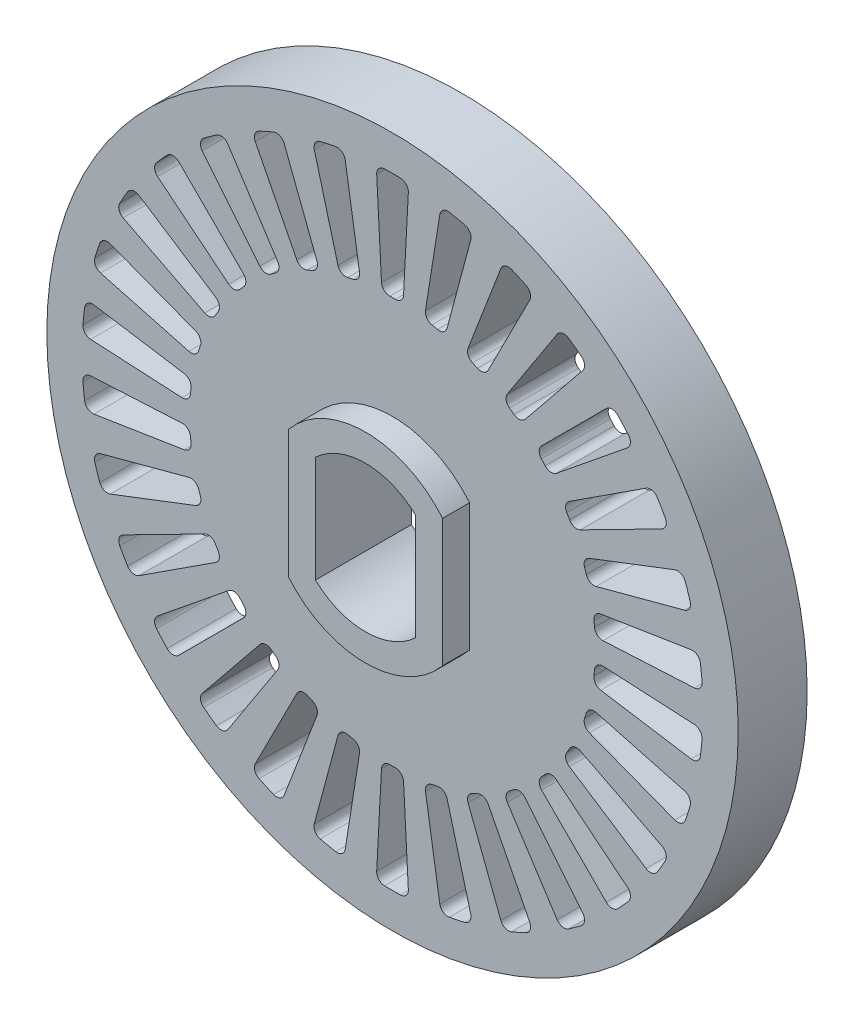
SolidWorks part; units mm, degrees
ref_plane "Plano frontal" through (0, 0, 0) normal (0, 0, 1) x (1, 0, 0)
ref_plane "Plano superior" through (0, 0, 0) normal (0, 1, 0) x (1, 0, 0)
ref_plane "Plano direito" through (0, 0, 0) normal (1, 0, 0) x (0, 0, -1)
sketch "Esboço1" plane through (0, 0, 0) normal (0, 0, 1) x (1, 0, 0)
  line L2 (-1.85, 1.9666) -> (-1.85, -1.9666)
  line L4 (1.85, 1.9666) -> (1.85, -1.9666)
  circle A0 centre (0, 0) radius 12.78
  arc A1 (-1.85, -1.9666) -> (1.85, -1.9666) centre (0, 0) ccw
  arc A2 (1.85, 1.9666) -> (-1.85, 1.9666) centre (0, 0) ccw
  dimension "D1" = 25.56
  dimension "D2" = 5.4
extrude "Ressalto-extrusão1" add sketch "Esboço1" along normal blind 2.55
sketch "Esboço2" plane through (0, 0, 0) normal (0, 0, 1) x (1, 0, 0)
  line L0 (-1.85, 1.9666) -> (-1.85, -1.9666) construction
  line L1 (1.85, -1.9666) -> (1.85, 1.9666) construction
  line L2 (1.85, -1.9666) -> (1.85, 1.9666)
  line L3 (-1.85, 1.9666) -> (-1.85, -1.9666)
  line L4 (-2.85, 2.3596) -> (-2.85, -2.3596)
  line L5 (2.85, -2.3596) -> (2.85, 2.3596)
  arc A0 (1.85, 1.9666) -> (-1.85, 1.9666) centre (0, 0) ccw construction
  circle A1 centre (0, 0) radius 12.78
  circle A2 centre (0, 0) radius 12.78
  arc A3 (-1.85, -1.9666) -> (1.85, -1.9666) centre (0, 0) ccw construction
  arc A4 (-1.85, -1.9666) -> (1.85, -1.9666) centre (0, 0) ccw
  arc A5 (1.85, 1.9666) -> (-1.85, 1.9666) centre (0, 0) ccw
  arc A6 (2.85, 2.3596) -> (-2.85, 2.3596) centre (0, 0) ccw
  arc A7 (-2.85, -2.3596) -> (2.85, -2.3596) centre (0, 0) ccw
  arc M21 (-1.85, -1.9666) -> (1.85, -1.9666) centre (0, 0) ccw
  line M22 (1.85, -1.9666) -> (1.85, 1.9666)
  arc M23 (1.85, 1.9666) -> (-1.85, 1.9666) centre (0, 0) ccw
  line M24 (-1.85, 1.9666) -> (-1.85, -1.9666)
  dimension "D1" = 0
  dimension "D2" = 1
extrude "Ressalto-extrusão2" add sketch "Esboço2" along normal blind 3.55 contours A7 L4 A6 L5 M24 M21 M22 M23
sketch "Esboço3" plane through (0, 0, 2.55) normal (0, 0, 1) x (1, 0, 0)
  line L0 (0, 0) -> (0, 12.78) construction
  line L1 (0.4079, 7.7835) -> (0.5849, 11.1607)
  line L2 (-0.4079, 7.7835) -> (-0.5849, 11.1607)
  line L3 (2.0173, 7.5286) -> (2.8926, 10.7952)
  line L4 (1.2193, 7.6983) -> (1.7483, 11.0384)
  line L5 (3.5385, 6.9447) -> (5.0738, 9.9579)
  line L6 (2.7932, 7.2765) -> (4.0051, 10.4337)
  line L7 (4.9051, 6.0573) -> (7.0333, 8.6854)
  line L8 (4.245, 6.5368) -> (6.0869, 9.373)
  line L9 (6.0573, 4.9051) -> (8.6854, 7.0333)
  line L10 (5.5114, 5.5114) -> (7.9026, 7.9026)
  line L11 (6.9447, 3.5385) -> (9.9579, 5.0738)
  line L12 (6.5368, 4.245) -> (9.373, 6.0869)
  line L13 (7.5286, 2.0173) -> (10.7952, 2.8926)
  line L14 (7.2765, 2.7932) -> (10.4337, 4.0051)
  line L15 (7.7835, 0.4079) -> (11.1607, 0.5849)
  line L16 (7.6983, 1.2193) -> (11.0384, 1.7483)
  line L17 (7.6983, -1.2193) -> (11.0384, -1.7483)
  line L18 (7.7835, -0.4079) -> (11.1607, -0.5849)
  line L19 (7.2765, -2.7932) -> (10.4337, -4.0051)
  line L20 (7.5286, -2.0173) -> (10.7952, -2.8926)
  line L21 (6.5368, -4.245) -> (9.373, -6.0869)
  line L22 (6.9447, -3.5385) -> (9.9579, -5.0738)
  line L23 (5.5114, -5.5114) -> (7.9026, -7.9026)
  line L24 (6.0573, -4.9051) -> (8.6854, -7.0333)
  line L25 (4.245, -6.5368) -> (6.0869, -9.373)
  line L26 (4.9051, -6.0573) -> (7.0333, -8.6854)
  line L27 (2.7932, -7.2765) -> (4.0051, -10.4337)
  line L28 (3.5385, -6.9447) -> (5.0738, -9.9579)
  line L29 (1.2193, -7.6983) -> (1.7483, -11.0384)
  line L30 (2.0173, -7.5286) -> (2.8926, -10.7952)
  line L31 (-0.4079, -7.7835) -> (-0.5849, -11.1607)
  line L32 (0.4079, -7.7835) -> (0.5849, -11.1607)
  line L33 (-2.0173, -7.5286) -> (-2.8926, -10.7952)
  line L34 (-1.2193, -7.6983) -> (-1.7483, -11.0384)
  line L35 (-3.5385, -6.9447) -> (-5.0738, -9.9579)
  line L36 (-2.7932, -7.2765) -> (-4.0051, -10.4337)
  line L37 (-4.9051, -6.0573) -> (-7.0333, -8.6854)
  line L38 (-4.245, -6.5368) -> (-6.0869, -9.373)
  line L39 (-6.0573, -4.9051) -> (-8.6854, -7.0333)
  line L40 (-5.5114, -5.5114) -> (-7.9026, -7.9026)
  line L41 (-6.9447, -3.5385) -> (-9.9579, -5.0738)
  line L42 (-6.5368, -4.245) -> (-9.373, -6.0869)
  line L43 (-7.5286, -2.0173) -> (-10.7952, -2.8926)
  line L44 (-7.2765, -2.7932) -> (-10.4337, -4.0051)
  line L45 (-7.7835, -0.4079) -> (-11.1607, -0.5849)
  line L46 (-7.6983, -1.2193) -> (-11.0384, -1.7483)
  line L47 (-7.6983, 1.2193) -> (-11.0384, 1.7483)
  line L48 (-7.7835, 0.4079) -> (-11.1607, 0.5849)
  line L49 (-7.2765, 2.7932) -> (-10.4337, 4.0051)
  line L50 (-7.5286, 2.0173) -> (-10.7952, 2.8926)
  line L51 (-6.5368, 4.245) -> (-9.373, 6.0869)
  line L52 (-6.9447, 3.5385) -> (-9.9579, 5.0738)
  line L53 (-5.5114, 5.5114) -> (-7.9026, 7.9026)
  line L54 (-6.0573, 4.9051) -> (-8.6854, 7.0333)
  line L55 (-4.245, 6.5368) -> (-6.0869, 9.373)
  line L56 (-4.9051, 6.0573) -> (-7.0333, 8.6854)
  line L57 (-2.7932, 7.2765) -> (-4.0051, 10.4337)
  line L58 (-3.5385, 6.9447) -> (-5.0738, 9.9579)
  line L59 (-1.2193, 7.6983) -> (-1.7483, 11.0384)
  line L60 (-2.0173, 7.5286) -> (-2.8926, 10.7952)
  circle A0 centre (0, 0) radius 12.78 construction
  arc A1 (0.293, 11.4763) -> (-0.293, 11.4763) centre (0, 0) ccw
  arc A2 (0.1042, 7.4993) -> (-0.1042, 7.4993) centre (0, 0) ccw
  arc A3 (1.85, 1.9666) -> (-1.85, 1.9666) centre (0, 0) ccw construction
  arc A4 (0.4079, 7.7835) -> (0.1042, 7.4993) centre (0.1083, 7.7992) cw
  arc A5 (-0.4079, 7.7835) -> (-0.1042, 7.4993) centre (-0.1083, 7.7992) ccw
  arc A6 (0.5849, 11.1607) -> (0.293, 11.4763) centre (0.2853, 11.1764) ccw
  arc A7 (-0.5849, 11.1607) -> (-0.293, 11.4763) centre (-0.2853, 11.1764) cw
  arc A9 (2.6726, 11.1646) -> (2.0995, 11.2864) centre (0, 0) ccw
  arc A10 (1.6611, 7.3137) -> (1.4573, 7.3571) centre (0, 0) ccw
  arc A11 (2.0173, 7.5286) -> (1.6611, 7.3137) centre (1.7275, 7.6063) cw
  arc A12 (1.2193, 7.6983) -> (1.4573, 7.3571) centre (1.5156, 7.6513) ccw
  arc A13 (2.8926, 10.7952) -> (2.6726, 11.1646) centre (2.6028, 10.8728) ccw
  arc A14 (1.7483, 11.0384) -> (2.0995, 11.2864) centre (2.0446, 10.9914) cw
  arc A15 (4.9355, 10.3649) -> (4.4002, 10.6032) centre (0, 0) ccw
  arc A16 (3.1454, 6.8086) -> (2.9551, 6.8933) centre (0, 0) ccw
  arc A17 (3.5385, 6.9447) -> (3.1454, 6.8086) centre (3.2712, 7.0809) cw
  arc A18 (2.7932, 7.2765) -> (2.9551, 6.8933) centre (3.0733, 7.169) ccw
  arc A19 (5.0738, 9.9579) -> (4.9355, 10.3649) centre (4.8065, 10.0941) ccw
  arc A20 (4.0051, 10.4337) -> (4.4002, 10.6032) centre (4.2852, 10.3262) cw
  arc A21 (6.9826, 9.1123) -> (6.5086, 9.4567) centre (0, 0) ccw
  arc A22 (4.4922, 6.0058) -> (4.3237, 6.1283) centre (0, 0) ccw
  arc A23 (4.9051, 6.0573) -> (4.4922, 6.0058) centre (4.6719, 6.246) cw
  arc A24 (4.245, 6.5368) -> (4.3237, 6.1283) centre (4.4966, 6.3734) ccw
  arc A25 (7.0333, 8.6854) -> (6.9826, 9.1123) centre (6.8001, 8.8742) ccw
  arc A26 (6.0869, 9.373) -> (6.5086, 9.4567) centre (6.3385, 9.2096) cw
  arc A27 (8.7246, 7.4614) -> (8.3325, 7.8968) centre (0, 0) ccw
  arc A28 (5.6427, 4.9406) -> (5.5033, 5.0954) centre (0, 0) ccw
  arc A29 (6.0573, 4.9051) -> (5.6427, 4.9406) centre (5.8685, 5.1382) cw
  arc A30 (5.5114, 5.5114) -> (5.5033, 5.0954) centre (5.7235, 5.2992) ccw
  arc A31 (8.6854, 7.0333) -> (8.7246, 7.4614) centre (8.4966, 7.2664) ccw
  arc A32 (7.9026, 7.9026) -> (8.3325, 7.8968) centre (8.1147, 7.6905) cw
  arc A33 (10.0852, 5.4844) -> (9.7922, 5.9919) centre (0, 0) ccw
  arc A34 (6.5466, 3.6594) -> (6.4425, 3.8398) centre (0, 0) ccw
  arc A35 (6.9447, 3.5385) -> (6.5466, 3.6594) centre (6.8085, 3.8058) cw
  arc A36 (6.5368, 4.245) -> (6.4425, 3.8398) centre (6.7002, 3.9934) ccw
  arc A37 (9.9579, 5.0738) -> (10.0852, 5.4844) centre (9.8217, 5.3411) ccw
  arc A38 (9.373, 6.0869) -> (9.7922, 5.9919) centre (9.5364, 5.8353) cw
  arc A39 (11.0051, 3.2677) -> (10.824, 3.825) centre (0, 0) ccw
  arc A40 (7.1644, 2.2183) -> (7.1, 2.4165) centre (0, 0) ccw
  arc A41 (7.5286, 2.0173) -> (7.1644, 2.2183) centre (7.451, 2.3071) cw
  arc A42 (7.2765, 2.7932) -> (7.1, 2.4165) centre (7.384, 2.5131) ccw
  arc A43 (10.7952, 2.8926) -> (11.0051, 3.2677) centre (10.7175, 3.1823) ccw
  arc A44 (10.4337, 4.0051) -> (10.824, 3.825) centre (10.5412, 3.725) cw
  arc A45 (11.444, 0.9082) -> (11.3828, 1.491) centre (0, 0) ccw
  arc A46 (7.4691, 0.6803) -> (7.4473, 0.8875) centre (0, 0) ccw
  arc A47 (7.7835, 0.4079) -> (7.4691, 0.6803) centre (7.7678, 0.7075) cw
  arc A48 (7.6983, 1.2193) -> (7.4473, 0.8875) centre (7.7452, 0.923) ccw
  arc A49 (11.1607, 0.5849) -> (11.444, 0.9082) centre (11.145, 0.8845) ccw
  arc A50 (11.0384, 1.7483) -> (11.3828, 1.491) centre (11.0853, 1.452) cw
  arc A51 (11.3828, -1.491) -> (11.444, -0.9082) centre (0, 0) ccw
  arc A52 (7.4473, -0.8875) -> (7.4691, -0.6803) centre (0, 0) ccw
  arc A53 (7.6983, -1.2193) -> (7.4473, -0.8875) centre (7.7452, -0.923) cw
  arc A54 (7.7835, -0.4079) -> (7.4691, -0.6803) centre (7.7678, -0.7075) ccw
  arc A55 (11.0384, -1.7483) -> (11.3828, -1.491) centre (11.0853, -1.452) ccw
  arc A56 (11.1607, -0.5849) -> (11.444, -0.9082) centre (11.145, -0.8845) cw
  arc A57 (10.824, -3.825) -> (11.0051, -3.2677) centre (0, 0) ccw
  arc A58 (7.1, -2.4165) -> (7.1644, -2.2183) centre (0, 0) ccw
  arc A59 (7.2765, -2.7932) -> (7.1, -2.4165) centre (7.384, -2.5131) cw
  arc A60 (7.5286, -2.0173) -> (7.1644, -2.2183) centre (7.451, -2.3071) ccw
  arc A61 (10.4337, -4.0051) -> (10.824, -3.825) centre (10.5412, -3.725) ccw
  arc A62 (10.7952, -2.8926) -> (11.0051, -3.2677) centre (10.7175, -3.1823) cw
  arc A63 (9.7922, -5.9919) -> (10.0852, -5.4844) centre (0, 0) ccw
  arc A64 (6.4425, -3.8398) -> (6.5466, -3.6594) centre (0, 0) ccw
  arc A65 (6.5368, -4.245) -> (6.4425, -3.8398) centre (6.7002, -3.9934) cw
  arc A66 (6.9447, -3.5385) -> (6.5466, -3.6594) centre (6.8085, -3.8058) ccw
  arc A67 (9.373, -6.0869) -> (9.7922, -5.9919) centre (9.5364, -5.8353) ccw
  arc A68 (9.9579, -5.0738) -> (10.0852, -5.4844) centre (9.8217, -5.3411) cw
  arc A69 (8.3325, -7.8968) -> (8.7246, -7.4614) centre (0, 0) ccw
  arc A70 (5.5033, -5.0954) -> (5.6427, -4.9406) centre (0, 0) ccw
  arc A71 (5.5114, -5.5114) -> (5.5033, -5.0954) centre (5.7235, -5.2992) cw
  arc A72 (6.0573, -4.9051) -> (5.6427, -4.9406) centre (5.8685, -5.1382) ccw
  arc A73 (7.9026, -7.9026) -> (8.3325, -7.8968) centre (8.1147, -7.6905) ccw
  arc A74 (8.6854, -7.0333) -> (8.7246, -7.4614) centre (8.4966, -7.2664) cw
  arc A75 (6.5086, -9.4567) -> (6.9826, -9.1123) centre (0, 0) ccw
  arc A76 (4.3237, -6.1283) -> (4.4922, -6.0058) centre (0, 0) ccw
  arc A77 (4.245, -6.5368) -> (4.3237, -6.1283) centre (4.4966, -6.3734) cw
  arc A78 (4.9051, -6.0573) -> (4.4922, -6.0058) centre (4.6719, -6.246) ccw
  arc A79 (6.0869, -9.373) -> (6.5086, -9.4567) centre (6.3385, -9.2096) ccw
  arc A80 (7.0333, -8.6854) -> (6.9826, -9.1123) centre (6.8001, -8.8742) cw
  arc A81 (4.4002, -10.6032) -> (4.9355, -10.3649) centre (0, 0) ccw
  arc A82 (2.9551, -6.8933) -> (3.1454, -6.8086) centre (0, 0) ccw
  arc A83 (2.7932, -7.2765) -> (2.9551, -6.8933) centre (3.0733, -7.169) cw
  arc A84 (3.5385, -6.9447) -> (3.1454, -6.8086) centre (3.2712, -7.0809) ccw
  arc A85 (4.0051, -10.4337) -> (4.4002, -10.6032) centre (4.2852, -10.3262) ccw
  arc A86 (5.0738, -9.9579) -> (4.9355, -10.3649) centre (4.8065, -10.0941) cw
  arc A87 (2.0995, -11.2864) -> (2.6726, -11.1646) centre (0, 0) ccw
  arc A88 (1.4573, -7.3571) -> (1.6611, -7.3137) centre (0, 0) ccw
  arc A89 (1.2193, -7.6983) -> (1.4573, -7.3571) centre (1.5156, -7.6513) cw
  arc A90 (2.0173, -7.5286) -> (1.6611, -7.3137) centre (1.7275, -7.6063) ccw
  arc A91 (1.7483, -11.0384) -> (2.0995, -11.2864) centre (2.0446, -10.9914) ccw
  arc A92 (2.8926, -10.7952) -> (2.6726, -11.1646) centre (2.6028, -10.8728) cw
  arc A93 (-0.293, -11.4763) -> (0.293, -11.4763) centre (0, 0) ccw
  arc A94 (-0.1042, -7.4993) -> (0.1042, -7.4993) centre (0, 0) ccw
  arc A95 (-0.4079, -7.7835) -> (-0.1042, -7.4993) centre (-0.1083, -7.7992) cw
  arc A96 (0.4079, -7.7835) -> (0.1042, -7.4993) centre (0.1083, -7.7992) ccw
  arc A97 (-0.5849, -11.1607) -> (-0.293, -11.4763) centre (-0.2853, -11.1764) ccw
  arc A98 (0.5849, -11.1607) -> (0.293, -11.4763) centre (0.2853, -11.1764) cw
  arc A99 (-2.6726, -11.1646) -> (-2.0995, -11.2864) centre (0, 0) ccw
  arc A100 (-1.6611, -7.3137) -> (-1.4573, -7.3571) centre (0, 0) ccw
  arc A101 (-2.0173, -7.5286) -> (-1.6611, -7.3137) centre (-1.7275, -7.6063) cw
  arc A102 (-1.2193, -7.6983) -> (-1.4573, -7.3571) centre (-1.5156, -7.6513) ccw
  arc A103 (-2.8926, -10.7952) -> (-2.6726, -11.1646) centre (-2.6028, -10.8728) ccw
  arc A104 (-1.7483, -11.0384) -> (-2.0995, -11.2864) centre (-2.0446, -10.9914) cw
  arc A105 (-4.9355, -10.3649) -> (-4.4002, -10.6032) centre (0, 0) ccw
  arc A106 (-3.1454, -6.8086) -> (-2.9551, -6.8933) centre (0, 0) ccw
  arc A107 (-3.5385, -6.9447) -> (-3.1454, -6.8086) centre (-3.2712, -7.0809) cw
  arc A108 (-2.7932, -7.2765) -> (-2.9551, -6.8933) centre (-3.0733, -7.169) ccw
  arc A109 (-5.0738, -9.9579) -> (-4.9355, -10.3649) centre (-4.8065, -10.0941) ccw
  arc A110 (-4.0051, -10.4337) -> (-4.4002, -10.6032) centre (-4.2852, -10.3262) cw
  arc A111 (-6.9826, -9.1123) -> (-6.5086, -9.4567) centre (0, 0) ccw
  arc A112 (-4.4922, -6.0058) -> (-4.3237, -6.1283) centre (0, 0) ccw
  arc A113 (-4.9051, -6.0573) -> (-4.4922, -6.0058) centre (-4.6719, -6.246) cw
  arc A114 (-4.245, -6.5368) -> (-4.3237, -6.1283) centre (-4.4966, -6.3734) ccw
  arc A115 (-7.0333, -8.6854) -> (-6.9826, -9.1123) centre (-6.8001, -8.8742) ccw
  arc A116 (-6.0869, -9.373) -> (-6.5086, -9.4567) centre (-6.3385, -9.2096) cw
  arc A117 (-8.7246, -7.4614) -> (-8.3325, -7.8968) centre (0, 0) ccw
  arc A118 (-5.6427, -4.9406) -> (-5.5033, -5.0954) centre (0, 0) ccw
  arc A119 (-6.0573, -4.9051) -> (-5.6427, -4.9406) centre (-5.8685, -5.1382) cw
  arc A120 (-5.5114, -5.5114) -> (-5.5033, -5.0954) centre (-5.7235, -5.2992) ccw
  arc A121 (-8.6854, -7.0333) -> (-8.7246, -7.4614) centre (-8.4966, -7.2664) ccw
  arc A122 (-7.9026, -7.9026) -> (-8.3325, -7.8968) centre (-8.1147, -7.6905) cw
  arc A123 (-10.0852, -5.4844) -> (-9.7922, -5.9919) centre (0, 0) ccw
  arc A124 (-6.5466, -3.6594) -> (-6.4425, -3.8398) centre (0, 0) ccw
  arc A125 (-6.9447, -3.5385) -> (-6.5466, -3.6594) centre (-6.8085, -3.8058) cw
  arc A126 (-6.5368, -4.245) -> (-6.4425, -3.8398) centre (-6.7002, -3.9934) ccw
  arc A127 (-9.9579, -5.0738) -> (-10.0852, -5.4844) centre (-9.8217, -5.3411) ccw
  arc A128 (-9.373, -6.0869) -> (-9.7922, -5.9919) centre (-9.5364, -5.8353) cw
  arc A129 (-11.0051, -3.2677) -> (-10.824, -3.825) centre (0, 0) ccw
  arc A130 (-7.1644, -2.2183) -> (-7.1, -2.4165) centre (0, 0) ccw
  arc A131 (-7.5286, -2.0173) -> (-7.1644, -2.2183) centre (-7.451, -2.3071) cw
  arc A132 (-7.2765, -2.7932) -> (-7.1, -2.4165) centre (-7.384, -2.5131) ccw
  arc A133 (-10.7952, -2.8926) -> (-11.0051, -3.2677) centre (-10.7175, -3.1823) ccw
  arc A134 (-10.4337, -4.0051) -> (-10.824, -3.825) centre (-10.5412, -3.725) cw
  arc A135 (-11.444, -0.9082) -> (-11.3828, -1.491) centre (0, 0) ccw
  arc A136 (-7.4691, -0.6803) -> (-7.4473, -0.8875) centre (0, 0) ccw
  arc A137 (-7.7835, -0.4079) -> (-7.4691, -0.6803) centre (-7.7678, -0.7075) cw
  arc A138 (-7.6983, -1.2193) -> (-7.4473, -0.8875) centre (-7.7452, -0.923) ccw
  arc A139 (-11.1607, -0.5849) -> (-11.444, -0.9082) centre (-11.145, -0.8845) ccw
  arc A140 (-11.0384, -1.7483) -> (-11.3828, -1.491) centre (-11.0853, -1.452) cw
  arc A141 (-11.3828, 1.491) -> (-11.444, 0.9082) centre (0, 0) ccw
  arc A142 (-7.4473, 0.8875) -> (-7.4691, 0.6803) centre (0, 0) ccw
  arc A143 (-7.6983, 1.2193) -> (-7.4473, 0.8875) centre (-7.7452, 0.923) cw
  arc A144 (-7.7835, 0.4079) -> (-7.4691, 0.6803) centre (-7.7678, 0.7075) ccw
  arc A145 (-11.0384, 1.7483) -> (-11.3828, 1.491) centre (-11.0853, 1.452) ccw
  arc A146 (-11.1607, 0.5849) -> (-11.444, 0.9082) centre (-11.145, 0.8845) cw
  arc A147 (-10.824, 3.825) -> (-11.0051, 3.2677) centre (0, 0) ccw
  arc A148 (-7.1, 2.4165) -> (-7.1644, 2.2183) centre (0, 0) ccw
  arc A149 (-7.2765, 2.7932) -> (-7.1, 2.4165) centre (-7.384, 2.5131) cw
  arc A150 (-7.5286, 2.0173) -> (-7.1644, 2.2183) centre (-7.451, 2.3071) ccw
  arc A151 (-10.4337, 4.0051) -> (-10.824, 3.825) centre (-10.5412, 3.725) ccw
  arc A152 (-10.7952, 2.8926) -> (-11.0051, 3.2677) centre (-10.7175, 3.1823) cw
  arc A153 (-9.7922, 5.9919) -> (-10.0852, 5.4844) centre (0, 0) ccw
  arc A154 (-6.4425, 3.8398) -> (-6.5466, 3.6594) centre (0, 0) ccw
  arc A155 (-6.5368, 4.245) -> (-6.4425, 3.8398) centre (-6.7002, 3.9934) cw
  arc A156 (-6.9447, 3.5385) -> (-6.5466, 3.6594) centre (-6.8085, 3.8058) ccw
  arc A157 (-9.373, 6.0869) -> (-9.7922, 5.9919) centre (-9.5364, 5.8353) ccw
  arc A158 (-9.9579, 5.0738) -> (-10.0852, 5.4844) centre (-9.8217, 5.3411) cw
  arc A159 (-8.3325, 7.8968) -> (-8.7246, 7.4614) centre (0, 0) ccw
  arc A160 (-5.5033, 5.0954) -> (-5.6427, 4.9406) centre (0, 0) ccw
  arc A161 (-5.5114, 5.5114) -> (-5.5033, 5.0954) centre (-5.7235, 5.2992) cw
  arc A162 (-6.0573, 4.9051) -> (-5.6427, 4.9406) centre (-5.8685, 5.1382) ccw
  arc A163 (-7.9026, 7.9026) -> (-8.3325, 7.8968) centre (-8.1147, 7.6905) ccw
  arc A164 (-8.6854, 7.0333) -> (-8.7246, 7.4614) centre (-8.4966, 7.2664) cw
  arc A165 (-6.5086, 9.4567) -> (-6.9826, 9.1123) centre (0, 0) ccw
  arc A166 (-4.3237, 6.1283) -> (-4.4922, 6.0058) centre (0, 0) ccw
  arc A167 (-4.245, 6.5368) -> (-4.3237, 6.1283) centre (-4.4966, 6.3734) cw
  arc A168 (-4.9051, 6.0573) -> (-4.4922, 6.0058) centre (-4.6719, 6.246) ccw
  arc A169 (-6.0869, 9.373) -> (-6.5086, 9.4567) centre (-6.3385, 9.2096) ccw
  arc A170 (-7.0333, 8.6854) -> (-6.9826, 9.1123) centre (-6.8001, 8.8742) cw
  arc A171 (-4.4002, 10.6032) -> (-4.9355, 10.3649) centre (0, 0) ccw
  arc A172 (-2.9551, 6.8933) -> (-3.1454, 6.8086) centre (0, 0) ccw
  arc A173 (-2.7932, 7.2765) -> (-2.9551, 6.8933) centre (-3.0733, 7.169) cw
  arc A174 (-3.5385, 6.9447) -> (-3.1454, 6.8086) centre (-3.2712, 7.0809) ccw
  arc A175 (-4.0051, 10.4337) -> (-4.4002, 10.6032) centre (-4.2852, 10.3262) ccw
  arc A176 (-5.0738, 9.9579) -> (-4.9355, 10.3649) centre (-4.8065, 10.0941) cw
  arc A177 (-2.0995, 11.2864) -> (-2.6726, 11.1646) centre (0, 0) ccw
  arc A178 (-1.4573, 7.3571) -> (-1.6611, 7.3137) centre (0, 0) ccw
  arc A179 (-1.2193, 7.6983) -> (-1.4573, 7.3571) centre (-1.5156, 7.6513) cw
  arc A180 (-2.0173, 7.5286) -> (-1.6611, 7.3137) centre (-1.7275, 7.6063) ccw
  arc A181 (-1.7483, 11.0384) -> (-2.0995, 11.2864) centre (-2.0446, 10.9914) ccw
  arc A182 (-2.8926, 10.7952) -> (-2.6726, 11.1646) centre (-2.6028, 10.8728) cw
  dimension "D1" = 1.3
  dimension "D2" = 4.8
  dimension "D5" = 0.3
  dimension "D3" = 3
  dimension "D4" = 3
  dimension "D6" = 30
extrude "Corte-extrusão1" cut sketch "Esboço3" against normal blind 3.55
